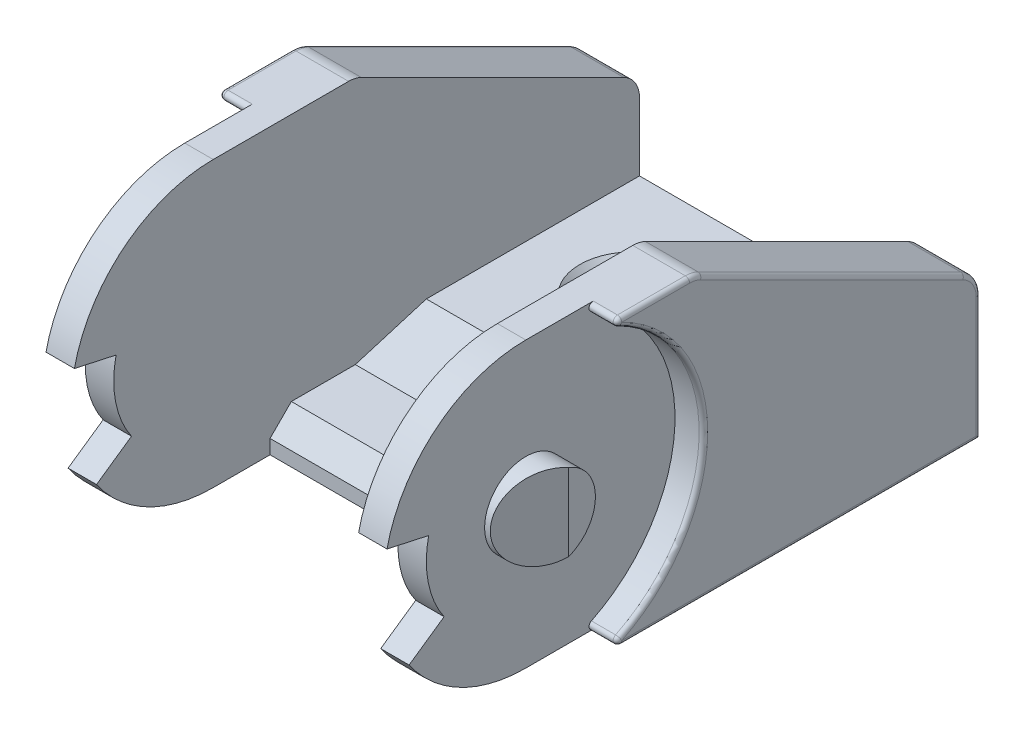
SolidWorks part; units mm, degrees
ref_plane "Front Plane" through (0, 0, 0) normal (0, 0, 1) x (1, 0, 0)
ref_plane "Top Plane" through (0, 0, 0) normal (0, 1, 0) x (1, 0, 0)
ref_plane "Right Plane" through (0, 0, 0) normal (1, 0, 0) x (0, 0, -1)
sketch "Sketch1" plane through (0, 0, 0) normal (1, 0, 0) x (0, 0, -1)
  line L1 (30, -10) -> (0, -10)
  line L2 (30, -10) -> (30, 10)
  line L3 (30, 10) -> (0, 10)
  line L4 (0, -10) -> (0, 10) construction
  arc A0 (0, 10) -> (0, -10) centre (0, 0) ccw
  dimension "D4" = 40
  dimension "D3" = 20
extrude "Boss-Extrude1" add sketch "Sketch1" along normal mid plane 28
sketch "Sketch2" plane through (14, 0, 0) normal (1, 0, 0) x (0, 0, -1)
  line L0 (30, 0) -> (10, 10)
  line L1 (30, -10) -> (30, 10) construction
  line L2 (30, 10) -> (0, 10) construction
  line L3 (10, 10) -> (30, 10)
  line L4 (30, 10) -> (30, 0)
  circle A0 centre (0, 0) radius 2.9
  dimension "D2" = 5.8
  dimension "D1" = 20
extrude "Cut-Extrude1" cut sketch "Sketch2" against normal blind 48
sketch "Sketch4" plane through (0, 0, 0) normal (1, 0, 0) x (0, 0, -1)
  line L16 (0, -10) -> (30, -10) construction
  line L17 (30, -10) -> (30, 0) construction
  line L18 (10, 10) -> (30, 0) construction
  line L19 (0, -10) -> (4, -10)
  line L20 (30, -6) -> (30, 0)
  line L21 (10, 10) -> (30, 0)
  line L26 (10, -7.5) -> (4, -7.5)
  line L27 (4, -7.5) -> (4, -10)
  line L28 (4, 7.5) -> (4, -7.5) construction
  line L29 (0, 10) -> (10, 10)
  line L30 (0, 10) -> (0, 7.5) construction
  line L31 (0, 7.5) -> (10, 7.5) construction
  line L32 (10, 7.5) -> (10, 10) construction
  line L33 (0, 0) -> (4, 0) construction
  line L34 (10, -7.5) -> (15, -6)
  line L35 (15, -6) -> (30, -6)
  arc A2 (0, 10) -> (0, -10) centre (0, 0) ccw construction
  arc A3 (0, 10) -> (0, -10) centre (0, 0) ccw
  dimension "D1" = 4
  dimension "D2" = 15
  dimension "D3" = 4
  dimension "D4" = 15
  dimension "D5" = 5
extrude "Cut-Extrude2" cut sketch "Sketch4" against normal mid plane 20
sketch "Sketch6" plane through (-14, 0, 0) normal (1, 0, 0) x (0, 0, -1)
  circle A1 centre (0, 0) radius 10.5
  dimension "D1" = 21
extrude "Cut-Extrude4" cut sketch "Sketch6" along normal blind 2
sketch "Sketch8" plane through (-10, 0, 0) normal (1, 0, 0) x (0, 0, -1)
  circle A0 centre (0, 0) radius 2.9 construction
  circle A1 centre (0, 0) radius 2.9
extrude "Boss-Extrude2" add sketch "Sketch8" against normal blind 4
sketch "Sketch9" plane through (0, 10, 0) normal (0, 1, 0) x (1, 0, 0)
  line L0 (-14, 1) -> (-14, -2.9)
  line L1 (-14, 2.9) -> (-14, -2.9) construction
  line L2 (-14, -2.9) -> (-12, -2.9) construction
  line L3 (-14, -2.9) -> (-12.4, -2.9)
  line L4 (-12.4, -2.9) -> (-14, 1)
  dimension "D1" = 1.6
  dimension "D2" = 3.9
extrude "Cut-Extrude6" cut sketch "Sketch9" against normal through all
mirror "Mirror1" about plane through (0, 0, 0) normal (1, 0, 0) of "Cut-Extrude6", "Boss-Extrude2", "Cut-Extrude4"
fillet "Fillet1" radius 0.3 4 edges at (13, 10, -3.2016) (13, -10, -3.2016) (-13, -10, -3.2016) (-13, 10, -3.2016)
sketch "Sketch5" plane through (0, -10, 0) normal (0, 1, 0) x (1, 0, 0)
  line L0 (-3, 22.5) -> (3, 22.5) construction
  line L1 (-3, 24.2) -> (3, 24.2)
  line L2 (-3, 20.8) -> (3, 20.8)
  line L3 (0, 22.5) -> (0, 0) construction
  line L5 (3, 22.5) -> (10, 22.5) construction
  line L6 (10, 15) -> (10, 30) construction
  arc A0 (-3, 24.2) -> (-3, 20.8) centre (-3, 22.5) ccw
  arc A1 (3, 20.8) -> (3, 24.2) centre (3, 22.5) ccw
  point P2 (0, 22.5)
  dimension "D1" = 3.4
  dimension "D2" = 6
extrude "Cut-Extrude3" cut sketch "Sketch5" along normal up to surface (4 mm away) up to face at (0, -6, -22.5)
chamfer "Chamfer1" distance 2 angle 45 4 edges at (0, -6, -24.2) (4.7, -6, -22.5) (-4.7, -6, -22.5) (0, -6, -20.8)
fillet "Fillet2" radius 2 4 edges at (-12, 0, -30) (12, 0, -30) (-12, 10, -10) (12, 10, -10)
fillet "Fillet3" radius 0.3 18 edges at (-14, 10, -7.1383) (-14, -10, -17.3743) (-14, -5.618, -30) (-14, -0.1846, -29.7013) (-14, 5.1708, -19.6584) (14, -10, -17.3743) (14, 10, -7.1383) (14, 5.1708, -19.6584) (14, -0.1846, -29.7013) (14, -5.618, -30) (-14, 9.9465, -9.9874) (14, 9.9465, -9.9874) (-14, 0, -10.5) (-14, 9.7677, -4.4564) (-14, -9.7677, -4.4564) (14, -9.7677, -4.4564) (14, 0, -10.5) (14, 9.7677, -4.4564)
sketch "Sketch7" plane through (0, 0, 0) normal (-1, 0, 0) x (0, 0, 1)
  line L0 (9.7677, 2.1429) -> (6.8374, 1.5)
  line L1 (5.7492, -3.9933) -> (8.2132, -5.7047)
  line L2 (5.7492, -3.9933) -> (0, 0) construction
  line L3 (0, 0) -> (10, 0) construction
  line L4 (6.8374, 1.5) -> (0, 0) construction
  line L5 (9.7677, 2.1429) -> (8.2132, -5.7047) construction
  arc A0 (0, -10) -> (0, 10) centre (0, 0) ccw construction
  arc A1 (5.7492, -3.9933) -> (6.8374, 1.5) centre (0, 0) ccw
  arc A2 (8.2132, -5.7047) -> (9.7677, 2.1429) centre (0, 0) ccw
  dimension "D1" = 1.5
  dimension "D2" = 3
  dimension "D3" = 8
extrude "Cut-Extrude5" cut sketch "Sketch7" against normal through all both and the other way through all
chamfer "Chamfer2" distance 1.5 angle 45 1 edges at (0, -7.5, -4)
